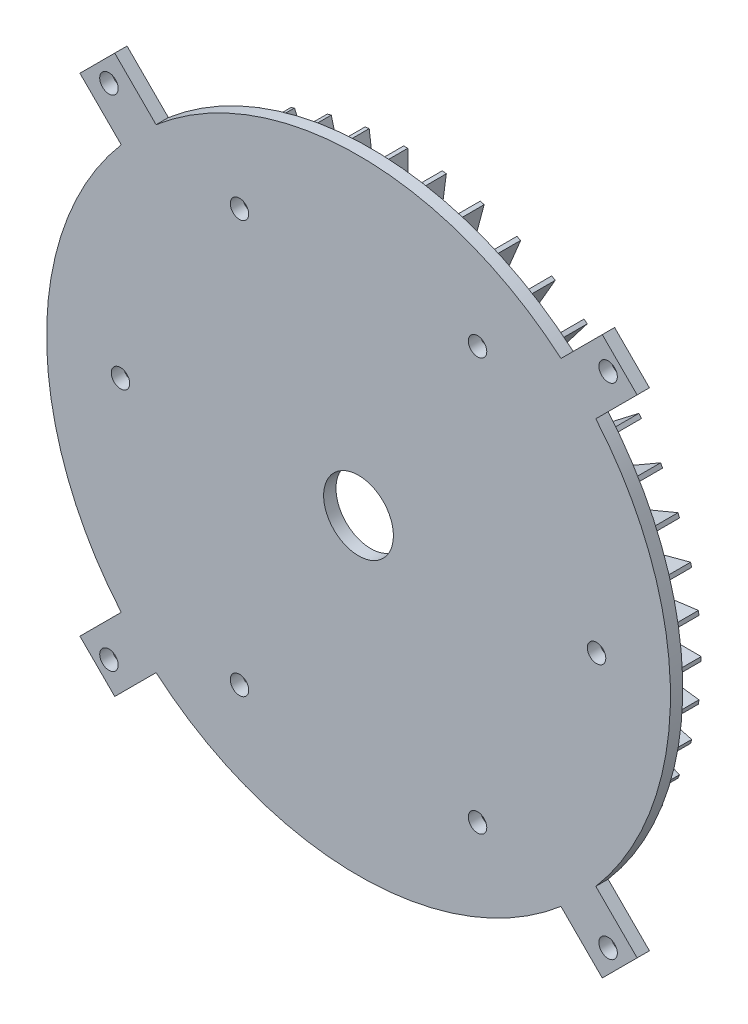
SolidWorks part; units mm, degrees
ref_plane "Спереди" through (0, 0, 0) normal (0, 0, 1) x (1, 0, 0)
ref_plane "Сверху" through (0, 0, 0) normal (0, 1, 0) x (1, 0, 0)
ref_plane "Справа" through (0, 0, 0) normal (1, 0, 0) x (0, 0, -1)
sketch "Эскиз1" plane through (0, 0, 0) normal (0, 0, 1) x (1, 0, 0)
  circle A0 centre (0, 0) radius 76
  circle A1 centre (0, 0) radius 8.5
extrude "Heat_spreader" add sketch "Эскиз1" along normal blind 3 from offset 35
sketch "Эскиз2" plane through (0, 0, 0) normal (0, 0, 1) x (1, 0, 0)
  line L0 (53.7401, 45.2548) -> (67.8823, 59.397)
  line L1 (67.8823, 59.397) -> (59.397, 67.8823)
  line L2 (59.397, 67.8823) -> (45.2548, 53.7401)
  line L3 (45.2548, 53.7401) -> (53.7401, 45.2548)
  line L4 (-45.2548, 53.7401) -> (-59.397, 67.8823)
  line L5 (-59.397, 67.8823) -> (-67.8823, 59.397)
  line L6 (-67.8823, 59.397) -> (-53.7401, 45.2548)
  line L7 (-53.7401, 45.2548) -> (-45.2548, 53.7401)
  line L8 (-53.7401, -45.2548) -> (-67.8823, -59.397)
  line L9 (-67.8823, -59.397) -> (-59.397, -67.8823)
  line L10 (-59.397, -67.8823) -> (-45.2548, -53.7401)
  line L11 (-45.2548, -53.7401) -> (-53.7401, -45.2548)
  line L12 (45.2548, -53.7401) -> (59.397, -67.8823)
  line L13 (59.397, -67.8823) -> (67.8823, -59.397)
  line L14 (67.8823, -59.397) -> (53.7401, -45.2548)
  line L15 (53.7401, -45.2548) -> (45.2548, -53.7401)
extrude "Tie_rod_ears" add sketch "Эскиз2" along normal blind 3 from offset 35
sketch "Эскиз3" plane through (0, 0, 0) normal (0, 0, 1) x (1, 0, 0)
  line L0 (26, -0.5) -> (72, -0.5)
  line L1 (72, -0.5) -> (72, 0.5)
  line L2 (72, 0.5) -> (26, 0.5)
  line L3 (26, 0.5) -> (26, -0.5)
  line L4 (25.8428, 2.898) -> (71.4493, 8.9022)
  line L5 (71.4493, 8.9022) -> (71.3188, 9.8936)
  line L6 (71.3188, 9.8936) -> (25.7123, 3.8894)
  line L7 (25.7123, 3.8894) -> (25.8428, 2.898)
  line L8 (25.2435, 6.2463) -> (69.6761, 18.152)
  line L9 (69.6761, 18.152) -> (69.4172, 19.1179)
  line L10 (69.4172, 19.1179) -> (24.9847, 7.2123)
  line L11 (24.9847, 7.2123) -> (25.2435, 6.2463)
  line L12 (24.2122, 9.4878) -> (66.7107, 27.0913)
  line L13 (66.7107, 27.0913) -> (66.328, 28.0151)
  line L14 (66.328, 28.0151) -> (23.8295, 10.4117)
  line L15 (23.8295, 10.4117) -> (24.2122, 9.4878)
  line L16 (22.7667, 12.567) -> (62.6038, 35.567)
  line L17 (62.6038, 35.567) -> (62.1038, 36.433)
  line L18 (62.1038, 36.433) -> (22.2667, 13.433)
  line L19 (22.2667, 13.433) -> (22.7667, 12.567)
  line L20 (20.9316, 15.4311) -> (57.4258, 43.4341)
  line L21 (57.4258, 43.4341) -> (56.8171, 44.2275)
  line L22 (56.8171, 44.2275) -> (20.3228, 16.2245)
  line L23 (20.3228, 16.2245) -> (20.9316, 15.4311)
  line L24 (18.7383, 18.0312) -> (51.2652, 50.5581)
  line L25 (51.2652, 50.5581) -> (50.5581, 51.2652)
  line L26 (50.5581, 51.2652) -> (18.0312, 18.7383)
  line L27 (18.0312, 18.7383) -> (18.7383, 18.0312)
  line L28 (16.2245, 20.3228) -> (44.2275, 56.8171)
  line L29 (44.2275, 56.8171) -> (43.4341, 57.4258)
  line L30 (43.4341, 57.4258) -> (15.4311, 20.9316)
  line L31 (15.4311, 20.9316) -> (16.2245, 20.3228)
  line L32 (13.433, 22.2667) -> (36.433, 62.1038)
  line L33 (36.433, 62.1038) -> (35.567, 62.6038)
  line L34 (35.567, 62.6038) -> (12.567, 22.7667)
  line L35 (12.567, 22.7667) -> (13.433, 22.2667)
  line L36 (10.4117, 23.8295) -> (28.0151, 66.328)
  line L37 (28.0151, 66.328) -> (27.0913, 66.7107)
  line L38 (27.0913, 66.7107) -> (9.4878, 24.2122)
  line L39 (9.4878, 24.2122) -> (10.4117, 23.8295)
  line L40 (7.2123, 24.9847) -> (19.1179, 69.4172)
  line L41 (19.1179, 69.4172) -> (18.152, 69.6761)
  line L42 (18.152, 69.6761) -> (6.2463, 25.2435)
  line L43 (6.2463, 25.2435) -> (7.2123, 24.9847)
  line L44 (3.8894, 25.7123) -> (9.8936, 71.3188)
  line L45 (9.8936, 71.3188) -> (8.9022, 71.4493)
  line L46 (8.9022, 71.4493) -> (2.898, 25.8428)
  line L47 (2.898, 25.8428) -> (3.8894, 25.7123)
  line L48 (0.5, 26) -> (0.5, 72)
  line L49 (0.5, 72) -> (-0.5, 72)
  line L50 (-0.5, 72) -> (-0.5, 26)
  line L51 (-0.5, 26) -> (0.5, 26)
  line L52 (-2.898, 25.8428) -> (-8.9022, 71.4493)
  line L53 (-8.9022, 71.4493) -> (-9.8936, 71.3188)
  line L54 (-9.8936, 71.3188) -> (-3.8894, 25.7123)
  line L55 (-3.8894, 25.7123) -> (-2.898, 25.8428)
  line L56 (-6.2463, 25.2435) -> (-18.152, 69.6761)
  line L57 (-18.152, 69.6761) -> (-19.1179, 69.4172)
  line L58 (-19.1179, 69.4172) -> (-7.2123, 24.9847)
  line L59 (-7.2123, 24.9847) -> (-6.2463, 25.2435)
  line L60 (-9.4878, 24.2122) -> (-27.0913, 66.7107)
  line L61 (-27.0913, 66.7107) -> (-28.0151, 66.328)
  line L62 (-28.0151, 66.328) -> (-10.4117, 23.8295)
  line L63 (-10.4117, 23.8295) -> (-9.4878, 24.2122)
  line L64 (-12.567, 22.7667) -> (-35.567, 62.6038)
  line L65 (-35.567, 62.6038) -> (-36.433, 62.1038)
  line L66 (-36.433, 62.1038) -> (-13.433, 22.2667)
  line L67 (-13.433, 22.2667) -> (-12.567, 22.7667)
  line L68 (-15.4311, 20.9316) -> (-43.4341, 57.4258)
  line L69 (-43.4341, 57.4258) -> (-44.2275, 56.8171)
  line L70 (-44.2275, 56.8171) -> (-16.2245, 20.3228)
  line L71 (-16.2245, 20.3228) -> (-15.4311, 20.9316)
  line L72 (-18.0312, 18.7383) -> (-50.5581, 51.2652)
  line L73 (-50.5581, 51.2652) -> (-51.2652, 50.5581)
  line L74 (-51.2652, 50.5581) -> (-18.7383, 18.0312)
  line L75 (-18.7383, 18.0312) -> (-18.0312, 18.7383)
  line L76 (-20.3228, 16.2245) -> (-56.8171, 44.2275)
  line L77 (-56.8171, 44.2275) -> (-57.4258, 43.4341)
  line L78 (-57.4258, 43.4341) -> (-20.9316, 15.4311)
  line L79 (-20.9316, 15.4311) -> (-20.3228, 16.2245)
  line L80 (-22.2667, 13.433) -> (-62.1038, 36.433)
  line L81 (-62.1038, 36.433) -> (-62.6038, 35.567)
  line L82 (-62.6038, 35.567) -> (-22.7667, 12.567)
  line L83 (-22.7667, 12.567) -> (-22.2667, 13.433)
  line L84 (-23.8295, 10.4117) -> (-66.328, 28.0151)
  line L85 (-66.328, 28.0151) -> (-66.7107, 27.0913)
  line L86 (-66.7107, 27.0913) -> (-24.2122, 9.4878)
  line L87 (-24.2122, 9.4878) -> (-23.8295, 10.4117)
  line L88 (-24.9847, 7.2123) -> (-69.4172, 19.1179)
  line L89 (-69.4172, 19.1179) -> (-69.6761, 18.152)
  line L90 (-69.6761, 18.152) -> (-25.2435, 6.2463)
  line L91 (-25.2435, 6.2463) -> (-24.9847, 7.2123)
  line L92 (-25.7123, 3.8894) -> (-71.3188, 9.8936)
  line L93 (-71.3188, 9.8936) -> (-71.4493, 8.9022)
  line L94 (-71.4493, 8.9022) -> (-25.8428, 2.898)
  line L95 (-25.8428, 2.898) -> (-25.7123, 3.8894)
  line L96 (-26, 0.5) -> (-72, 0.5)
  line L97 (-72, 0.5) -> (-72, -0.5)
  line L98 (-72, -0.5) -> (-26, -0.5)
  line L99 (-26, -0.5) -> (-26, 0.5)
  line L100 (-25.8428, -2.898) -> (-71.4493, -8.9022)
  line L101 (-71.4493, -8.9022) -> (-71.3188, -9.8936)
  line L102 (-71.3188, -9.8936) -> (-25.7123, -3.8894)
  line L103 (-25.7123, -3.8894) -> (-25.8428, -2.898)
  line L104 (-25.2435, -6.2463) -> (-69.6761, -18.152)
  line L105 (-69.6761, -18.152) -> (-69.4172, -19.1179)
  line L106 (-69.4172, -19.1179) -> (-24.9847, -7.2123)
  line L107 (-24.9847, -7.2123) -> (-25.2435, -6.2463)
  line L108 (-24.2122, -9.4878) -> (-66.7107, -27.0913)
  line L109 (-66.7107, -27.0913) -> (-66.328, -28.0151)
  line L110 (-66.328, -28.0151) -> (-23.8295, -10.4117)
  line L111 (-23.8295, -10.4117) -> (-24.2122, -9.4878)
  line L112 (-22.7667, -12.567) -> (-62.6038, -35.567)
  line L113 (-62.6038, -35.567) -> (-62.1038, -36.433)
  line L114 (-62.1038, -36.433) -> (-22.2667, -13.433)
  line L115 (-22.2667, -13.433) -> (-22.7667, -12.567)
  line L116 (-20.9316, -15.4311) -> (-57.4258, -43.4341)
  line L117 (-57.4258, -43.4341) -> (-56.8171, -44.2275)
  line L118 (-56.8171, -44.2275) -> (-20.3228, -16.2245)
  line L119 (-20.3228, -16.2245) -> (-20.9316, -15.4311)
  line L120 (-18.7383, -18.0312) -> (-51.2652, -50.5581)
  line L121 (-51.2652, -50.5581) -> (-50.5581, -51.2652)
  line L122 (-50.5581, -51.2652) -> (-18.0312, -18.7383)
  line L123 (-18.0312, -18.7383) -> (-18.7383, -18.0312)
  line L124 (-16.2245, -20.3228) -> (-44.2275, -56.8171)
  line L125 (-44.2275, -56.8171) -> (-43.4341, -57.4258)
  line L126 (-43.4341, -57.4258) -> (-15.4311, -20.9316)
  line L127 (-15.4311, -20.9316) -> (-16.2245, -20.3228)
  line L128 (-13.433, -22.2667) -> (-36.433, -62.1038)
  line L129 (-36.433, -62.1038) -> (-35.567, -62.6038)
  line L130 (-35.567, -62.6038) -> (-12.567, -22.7667)
  line L131 (-12.567, -22.7667) -> (-13.433, -22.2667)
  line L132 (-10.4117, -23.8295) -> (-28.0151, -66.328)
  line L133 (-28.0151, -66.328) -> (-27.0913, -66.7107)
  line L134 (-27.0913, -66.7107) -> (-9.4878, -24.2122)
  line L135 (-9.4878, -24.2122) -> (-10.4117, -23.8295)
  line L136 (-7.2123, -24.9847) -> (-19.1179, -69.4172)
  line L137 (-19.1179, -69.4172) -> (-18.152, -69.6761)
  line L138 (-18.152, -69.6761) -> (-6.2463, -25.2435)
  line L139 (-6.2463, -25.2435) -> (-7.2123, -24.9847)
  line L140 (-3.8894, -25.7123) -> (-9.8936, -71.3188)
  line L141 (-9.8936, -71.3188) -> (-8.9022, -71.4493)
  line L142 (-8.9022, -71.4493) -> (-2.898, -25.8428)
  line L143 (-2.898, -25.8428) -> (-3.8894, -25.7123)
  line L144 (-0.5, -26) -> (-0.5, -72)
  line L145 (-0.5, -72) -> (0.5, -72)
  line L146 (0.5, -72) -> (0.5, -26)
  line L147 (0.5, -26) -> (-0.5, -26)
  line L148 (2.898, -25.8428) -> (8.9022, -71.4493)
  line L149 (8.9022, -71.4493) -> (9.8936, -71.3188)
  line L150 (9.8936, -71.3188) -> (3.8894, -25.7123)
  line L151 (3.8894, -25.7123) -> (2.898, -25.8428)
  line L152 (6.2463, -25.2435) -> (18.152, -69.6761)
  line L153 (18.152, -69.6761) -> (19.1179, -69.4172)
  line L154 (19.1179, -69.4172) -> (7.2123, -24.9847)
  line L155 (7.2123, -24.9847) -> (6.2463, -25.2435)
  line L156 (9.4878, -24.2122) -> (27.0913, -66.7107)
  line L157 (27.0913, -66.7107) -> (28.0151, -66.328)
  line L158 (28.0151, -66.328) -> (10.4117, -23.8295)
  line L159 (10.4117, -23.8295) -> (9.4878, -24.2122)
  line L160 (12.567, -22.7667) -> (35.567, -62.6038)
  line L161 (35.567, -62.6038) -> (36.433, -62.1038)
  line L162 (36.433, -62.1038) -> (13.433, -22.2667)
  line L163 (13.433, -22.2667) -> (12.567, -22.7667)
  line L164 (15.4311, -20.9316) -> (43.4341, -57.4258)
  line L165 (43.4341, -57.4258) -> (44.2275, -56.8171)
  line L166 (44.2275, -56.8171) -> (16.2245, -20.3228)
  line L167 (16.2245, -20.3228) -> (15.4311, -20.9316)
  line L168 (18.0312, -18.7383) -> (50.5581, -51.2652)
  line L169 (50.5581, -51.2652) -> (51.2652, -50.5581)
  line L170 (51.2652, -50.5581) -> (18.7383, -18.0312)
  line L171 (18.7383, -18.0312) -> (18.0312, -18.7383)
  line L172 (20.3228, -16.2245) -> (56.8171, -44.2275)
  line L173 (56.8171, -44.2275) -> (57.4258, -43.4341)
  line L174 (57.4258, -43.4341) -> (20.9316, -15.4311)
  line L175 (20.9316, -15.4311) -> (20.3228, -16.2245)
  line L176 (22.2667, -13.433) -> (62.1038, -36.433)
  line L177 (62.1038, -36.433) -> (62.6038, -35.567)
  line L178 (62.6038, -35.567) -> (22.7667, -12.567)
  line L179 (22.7667, -12.567) -> (22.2667, -13.433)
  line L180 (23.8295, -10.4117) -> (66.328, -28.0151)
  line L181 (66.328, -28.0151) -> (66.7107, -27.0913)
  line L182 (66.7107, -27.0913) -> (24.2122, -9.4878)
  line L183 (24.2122, -9.4878) -> (23.8295, -10.4117)
  line L184 (24.9847, -7.2123) -> (69.4172, -19.1179)
  line L185 (69.4172, -19.1179) -> (69.6761, -18.152)
  line L186 (69.6761, -18.152) -> (25.2435, -6.2463)
  line L187 (25.2435, -6.2463) -> (24.9847, -7.2123)
  line L188 (25.7123, -3.8894) -> (71.3188, -9.8936)
  line L189 (71.3188, -9.8936) -> (71.4493, -8.9022)
  line L190 (71.4493, -8.9022) -> (25.8428, -2.898)
  line L191 (25.8428, -2.898) -> (25.7123, -3.8894)
extrude "Cooling_fins" add sketch "Эскиз3" along normal blind 8.5 from offset 43.5
sketch "Эскиз4" plane through (0, 0, 0) normal (0, 0, 1) x (1, 0, 0)
  circle A0 centre (60.8112, 60.8112) radius 2.25
  circle A1 centre (-60.8112, 60.8112) radius 2.25
  circle A2 centre (-60.8112, -60.8112) radius 2.25
  circle A3 centre (60.8112, -60.8112) radius 2.25
  circle A4 centre (58, 0) radius 2.25
  circle A5 centre (29, 50.2295) radius 2.25
  circle A6 centre (-29, 50.2295) radius 2.25
  circle A7 centre (-58, 0) radius 2.25
  circle A8 centre (-29, -50.2295) radius 2.25
  circle A9 centre (29, -50.2295) radius 2.25
extrude "Through_holes" cut sketch "Эскиз4" against normal mid plane 200
